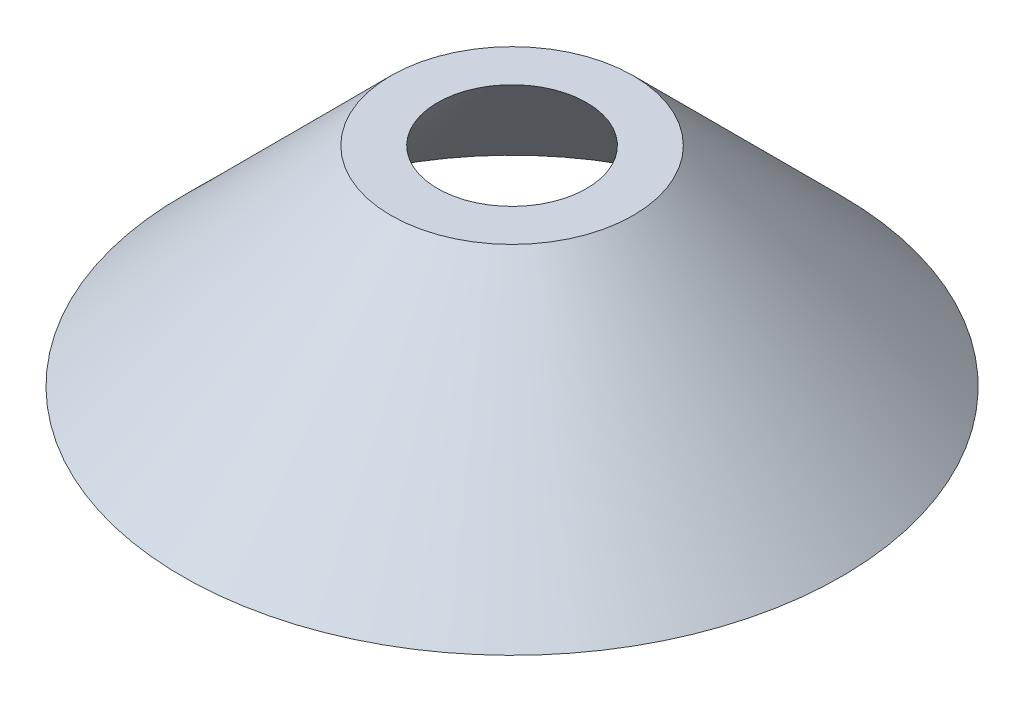
SolidWorks part; units mm, degrees
ref_plane "Front Plane" through (0, 0, 0) normal (0, 0, 1) x (1, 0, 0)
ref_plane "Top Plane" through (0, 0, 0) normal (0, 1, 0) x (1, 0, 0)
ref_plane "Right Plane" through (0, 0, 0) normal (1, 0, 0) x (0, 0, -1)
sketch "Sketch1" plane through (0, 0, 0) normal (0, 0, 1) x (1, 0, 0)
  line L0 (0, 0) -> (0, 61.7941) construction
  line L1 (-22.262, 38.3145) -> (-60.5765, 0)
  line L2 (0, 0) -> (26.7876, 0) construction
  line L3 (-22.262, 38.3145) -> (-13.6982, 38.3145)
  line L4 (-13.6982, 38.3145) -> (-52.0127, 0)
  line L5 (-52.0127, 0) -> (-60.5765, 0)
  dimension "D1" = 45
revolve "Revolve1" add sketch "Sketch1" angle 360 about L0
